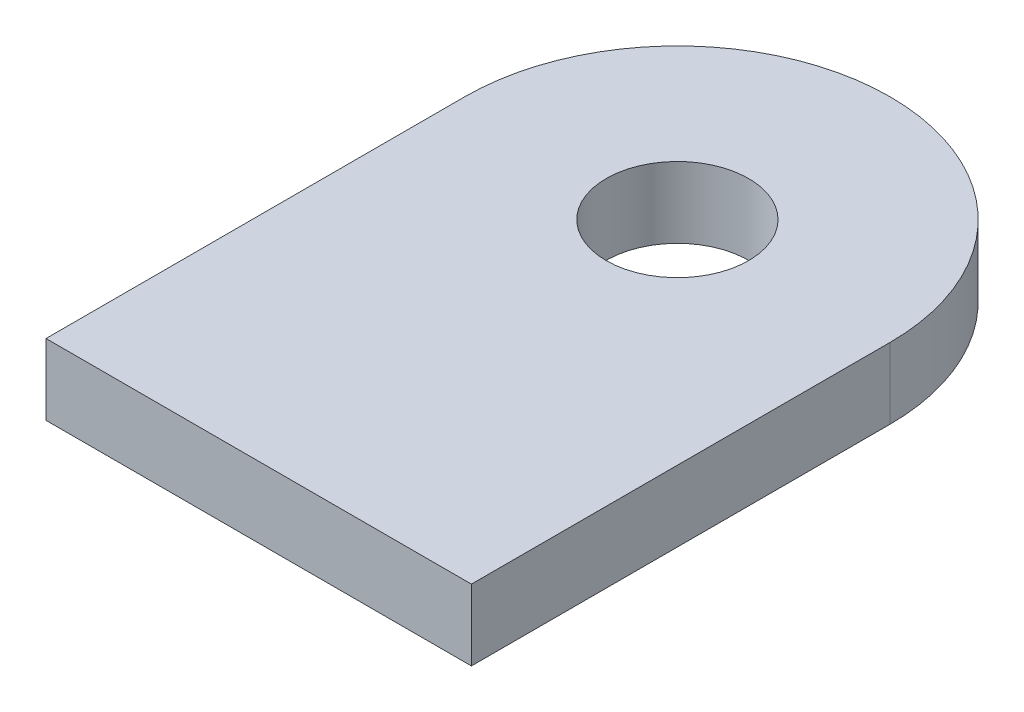
SolidWorks part; units mm, degrees
ref_plane "Front Plane" through (0, 0, 0) normal (0, 0, 1) x (1, 0, 0)
ref_plane "Top Plane" through (0, 0, 0) normal (0, 1, 0) x (1, 0, 0)
ref_plane "Right Plane" through (0, 0, 0) normal (1, 0, 0) x (0, 0, -1)
sketch "Sketch1" plane through (0, 0, 0) normal (0, 1, 0) x (1, 0, 0)
  line L1 (0, 0) -> (25.4, 0)
  line L2 (0, 0) -> (0, 25)
  line L3 (0, 25) -> (25.4, 25)
  line L4 (25.4, 0) -> (25.4, 25)
  arc A0 (0, 25) -> (25.4, 25) centre (12.7, 25) cw
  circle A1 centre (12.7, 25) radius 4.25
  dimension "D1" = 8.5
  dimension "D2" = 25.4
  dimension "D3" = 25
extrude "Boss-Extrude1" add sketch "Sketch1" along normal blind 4.2333 contours A1 L3 L2 L1 L4 | A1 L3 A0
